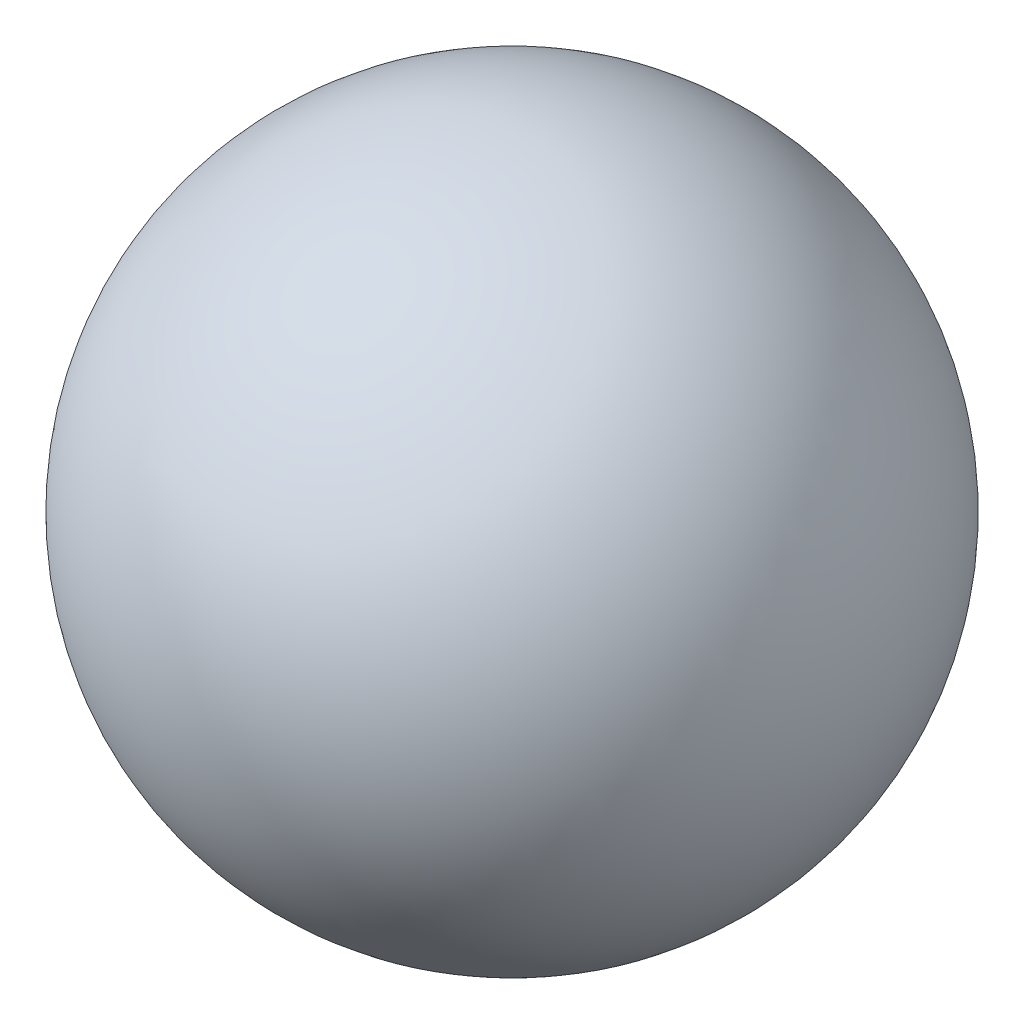
SolidWorks part; units mm, degrees
ref_plane "Front Plane" through (0, 0, 0) normal (0, 0, 1) x (1, 0, 0)
ref_plane "Top Plane" through (0, 0, 0) normal (0, 1, 0) x (1, 0, 0)
ref_plane "Right Plane" through (0, 0, 0) normal (1, 0, 0) x (0, 0, -1)
sketch "Sketch1" plane through (0, 0, 0) normal (0, 0, 1) x (1, 0, 0)
  line L0 (0, 10.9618) -> (0, -9.0623) construction
  circle A0 centre (0, 0) radius 7.14
  dimension "D1" = 14.28
revolve "Revolve1" add sketch "Sketch1" angle 360 about L0
